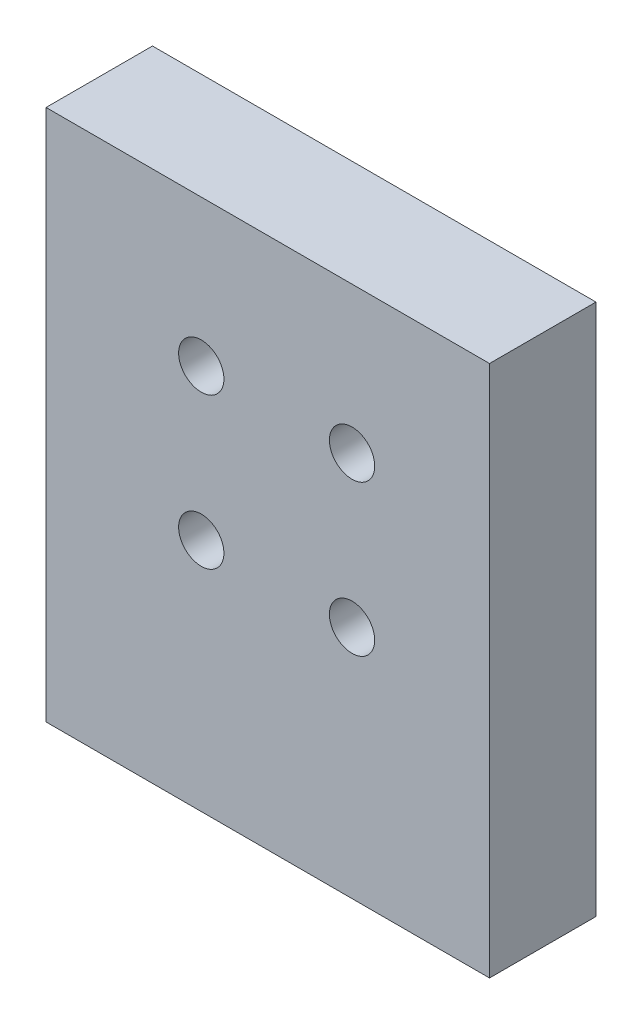
SolidWorks part; units mm, degrees
material "6061-T6 (SS)"
ref_plane "Front Plane" through (0, 0, 0) normal (0, 0, 1) x (1, 0, 0)
ref_plane "Top Plane" through (0, 0, 0) normal (0, 1, 0) x (1, 0, 0)
ref_plane "Right Plane" through (0, 0, 0) normal (1, 0, 0) x (0, 0, -1)
sketch "Sketch1" plane through (0, 0, 0) normal (0, 0, 1) x (1, 0, 0)
  line L1 (25, 30) -> (-25, 30)
  line L2 (25, 30) -> (25, -30)
  line L3 (25, -30) -> (-25, -30)
  line L4 (-25, 30) -> (-25, -30)
  line L5 (25, 30) -> (-25, -30) construction
  line L6 (25, -30) -> (-25, 30) construction
  point P0 (0, 0)
  dimension "D1" = 50
  dimension "D2" = 60
extrude "Boss-Extrude1" add sketch "Sketch1" along normal blind 12 contours L1 L4 L3 L2
hole_wizard "1/4-20 Tapped Hole1" positions "Sketch2" profile "Sketch3" tap size "1/4-20" standard "ANSI Inch"
sketch "Sketch2" plane through (0, 0, 12) normal (0, 0, 1) x (1, 0, 0)
  line L8 (25, -30) -> (25, 30)
  line L9 (25, 30) -> (-25, 30)
  line L10 (-25, 30) -> (-25, -30)
  line L11 (-25, -30) -> (25, -30)
  line L12 (25, -30) -> (25, 30)
  line L13 (25, 30) -> (-25, 30)
  line L14 (-25, 30) -> (-25, -30)
  line L15 (-25, -30) -> (25, -30)
  line L16 (10, -30) -> (10, 30)
  line L18 (-7.5, -30) -> (-7.5, 30) construction
  line L20 (-25, 0) -> (-7.5, 0) construction
  line L21 (-7.5, 0) -> (10, 0) construction
  line L23 (-7.5, 13.5) -> (9.5, 13.5) construction
  line L25 (-7.5, -3.5) -> (9.5, -3.5) construction
  point P0 (-7.5, 13.5)
  point P2 (9.5, 13.5)
  point P4 (9.5, -3.5)
  point P6 (-7.5, -3.5)
  dimension "D2" = 35
  dimension "D3" = 26.5
  dimension "D4" = 17
  dimension "D5" = 17
  dimension "D1" = 0
sketch "Sketch3" plane through (-7.5, 13.5, 12) normal (1, 0, 0) x (0, -1, 0)
  line L0 (0, 0) -> (0, 18.0438)
  line L1 (0, 18.0438) -> (2.5527, 16.51)
  line L2 (2.5527, 16.51) -> (2.5527, 0)
  line L5 (2.5527, 0) -> (0, 0)
  line L10 (0, 18.0438) -> (-2.5527, 16.51) construction
  line L11 (0, -6.35) -> (0, 107.95) construction
  dimension "Tap Drill Dia." = 5.1054
  dimension "Tap Drill Depth" = 16.51
  dimension "Drill Angle" = 118
cosmetic thread "Hole Thread4"
cosmetic thread "Hole Thread5"
cosmetic thread "Hole Thread6"
cosmetic thread "Hole Thread7"
hole_wizard "#8-32 Tapped Hole1" positions "Sketch4" profile "Sketch5" tap size "#8-32" standard "ANSI Inch"
sketch "Sketch4" plane through (0, -30, 0) normal (0, -1, 0) x (-1, 0, 0)
  line L8 (25, 0) -> (-25, 0)
  line L9 (-25, 0) -> (-25, -12)
  line L10 (-25, -12) -> (25, -12)
  line L11 (25, -12) -> (25, 0)
  line L12 (25, 0) -> (-25, 0)
  line L13 (-25, 0) -> (-25, -12)
  line L14 (-25, -12) -> (25, -12)
  line L15 (25, -12) -> (25, 0)
  line L16 (25, -6) -> (15, -6) construction
  line L18 (-15, -6) -> (-25, -6) construction
  line L20 (15, -6) -> (-15, -6) construction
  point P0 (15, -6)
  point P2 (0, -6)
  point P4 (-15, -6)
  dimension "D2" = 30
  dimension "D1" = 0
sketch "Sketch5" plane through (-15, -30, 6) normal (1, 0, 0) x (0, 0, -1)
  line L0 (0, 0) -> (0, 13.7378)
  line L1 (0, 13.7378) -> (1.7272, 12.7)
  line L2 (1.7272, 12.7) -> (1.7272, 0)
  line L5 (1.7272, 0) -> (0, 0)
  line L10 (0, 13.7378) -> (-1.7272, 12.7) construction
  line L11 (0, -6.35) -> (0, 107.95) construction
  dimension "Tap Drill Dia." = 3.4544
  dimension "Tap Drill Depth" = 12.7
  dimension "Drill Angle" = 118
cosmetic thread "Hole Thread1"
cosmetic thread "Hole Thread2"
cosmetic thread "Hole Thread3"
equation "\"OuterLegMountHoleDisplacement\"=30"
equation "\"D2@Sketch4\"=\"OuterLegMountHoleDisplacement\""
